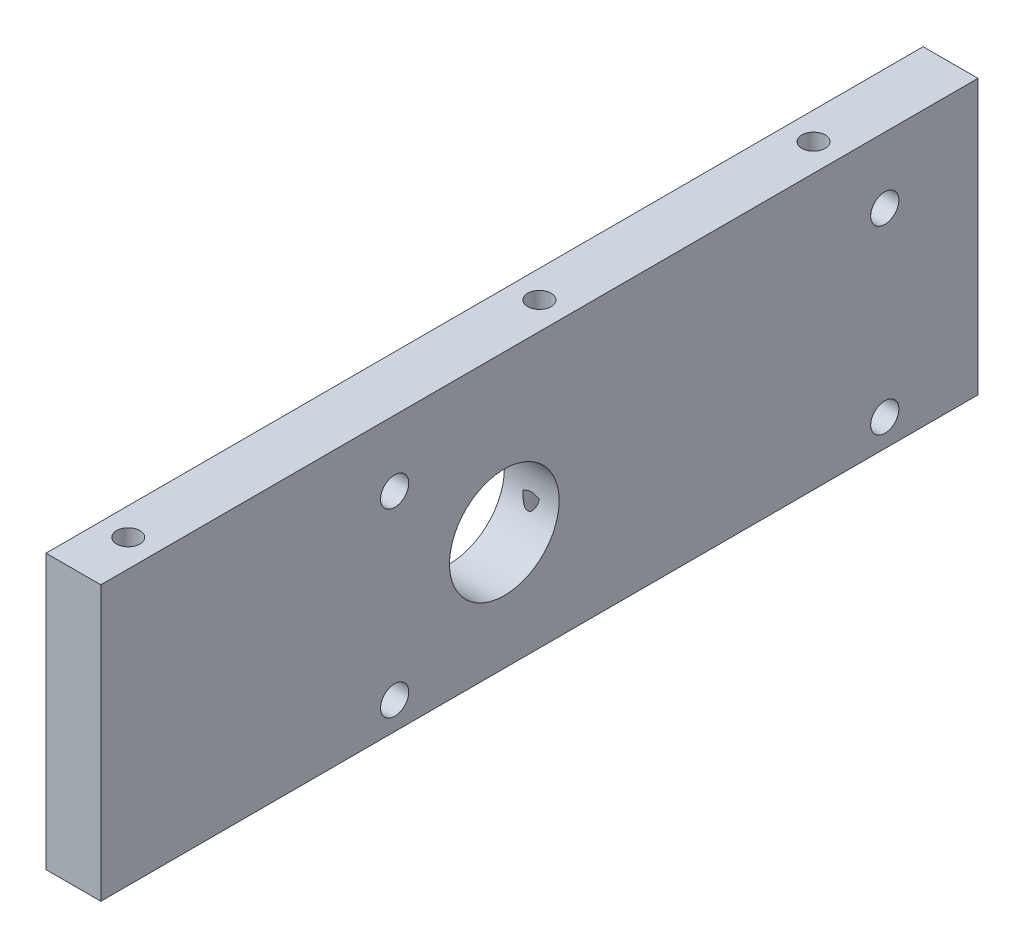
SolidWorks part; units mm, degrees
material "PE High Density"
ref_plane "Front Plane" through (0, 0, 0) normal (0, 0, 1) x (1, 0, 0)
ref_plane "Top Plane" through (0, 0, 0) normal (0, 1, 0) x (1, 0, 0)
ref_plane "Right Plane" through (0, 0, 0) normal (1, 0, 0) x (0, 0, -1)
sketch "Sketch1" plane through (0, 0, 0) normal (1, 0, 0) x (0, 0, -1)
  line L1 (-50.8, -15.875) -> (50.8, -15.875)
  line L2 (-50.8, -15.875) -> (-50.8, 15.875)
  line L3 (-50.8, 15.875) -> (50.8, 15.875)
  line L4 (50.8, -15.875) -> (50.8, 15.875)
  line L5 (-50.8, -15.875) -> (50.8, 15.875) construction
  line L6 (-50.8, 15.875) -> (50.8, -15.875) construction
  point P0 (0, 0)
  dimension "D1" = 101.6
  dimension "D2" = 31.75
extrude "Boss-Extrude1" add sketch "Sketch1" along normal mid plane 6.35
sketch "Sketch2" plane through (3.175, 0, 0) normal (1, 0, 0) x (0, 0, -1)
  line L0 (50.8, -15.875) -> (50.8, 15.875) construction
  line L1 (-16.764, -12.7) -> (40.005, -12.7) construction
  line L2 (-16.764, -12.7) -> (-16.764, 8.255) construction
  line L3 (-16.764, 8.255) -> (40.005, 8.255) construction
  line L4 (40.005, -12.7) -> (40.005, 8.255) construction
  line L5 (-16.764, -12.7) -> (40.005, 8.255) construction
  line L6 (-16.764, 8.255) -> (40.005, -12.7) construction
  line L7 (-50.8, -15.875) -> (50.8, -15.875) construction
  line L8 (11.6205, -2.2225) -> (-4.064, -2.2225) construction
  circle A0 centre (-16.764, 8.255) radius 1.632
  circle A1 centre (-16.764, -12.7) radius 1.632
  circle A2 centre (40.005, -12.7) radius 1.6319
  circle A3 centre (40.005, 8.255) radius 1.6319
  circle A4 centre (-4.064, -2.2225) radius 6.35
  point P0 (11.6205, -2.2225)
  point P3 (11.6205, -2.2225)
  dimension "D5" = 3.2639
  dimension "D6" = 15.6845
  dimension "D7" = 12.7
  dimension "D1" = 56.769
  dimension "D2" = 20.955
  dimension "D3" = 10.795
  dimension "D4" = 3.175
extrude "Cut-Extrude1" cut sketch "Sketch2" against normal up to next
sketch "Sketch3" plane through (0, 15.875, 0) normal (0, 1, 0) x (1, 0, 0)
  line L0 (0, 152.4) -> (0, -50.8) construction
  line L1 (3.175, 50.8) -> (-3.175, 50.8) construction
  line L2 (3.175, -50.8) -> (-3.175, -50.8) construction
  point P0 (0, -44.45)
  point P4 (0, 3.175)
  point P7 (0, 34.925)
  point P8 (0, 0)
  dimension "D1" = 15.875
  dimension "D2" = 31.75
  dimension "D3" = 6.35
hole_wizard "Tap Drill for #6-32 Tap1" positions "Sketch4" profile "Sketch5" hole size "#6-32" standard "ANSI Inch"
sketch "Sketch4" plane through (0, 15.875, 0) normal (0, 1, 0) x (1, 0, 0)
  point P0 (0, -44.45)
  point P3 (0, 34.925)
  point P12 (0, 3.175)
  point P20 (0, 0)
  point P21 (0, 0)
  point P22 (0, 0)
sketch "Sketch5" plane through (0, 15.875, 44.45) normal (1, 0, 0) x (0, 0, 1)
  line L0 (0, 0) -> (0, 13.5127)
  line L1 (0, 13.5127) -> (1.3525, 12.7)
  line L2 (1.3525, 12.7) -> (1.3525, 0)
  line L5 (1.3525, 0) -> (0, 0)
  line L10 (0, 13.5127) -> (-1.3526, 12.7) construction
  line L11 (0, -6.35) -> (0, 107.95) construction
  dimension "Hole Dia." = 2.7051
  dimension "Hole Depth" = 12.7
  dimension "Drill Angle" = 118
mirror "Mirror1" about plane through (0, 0, 0) normal (0, 1, 0) of "Tap Drill for #6-32 Tap1"
